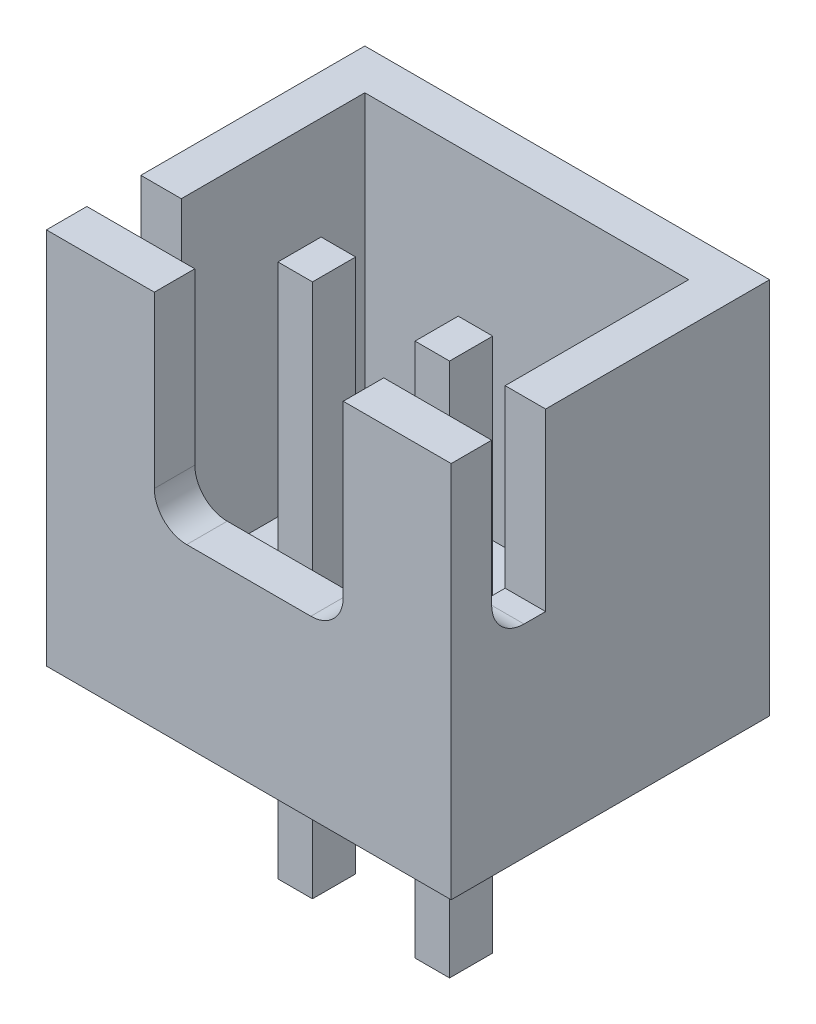
SolidWorks part; units mm, degrees
ref_plane "Alzado" through (0, 0, 0) normal (0, 0, 1) x (1, 0, 0)
ref_plane "Planta" through (0, 0, 0) normal (0, 1, 0) x (1, 0, 0)
ref_plane "Vista lateral" through (0, 0, 0) normal (1, 0, 0) x (0, 0, -1)
sketch "Croquis1" plane through (0, 0, 0) normal (0, 1, 0) x (1, 0, 0)
  line L0 (-2.48, 3.37) -> (5.02, 3.37)
  line L1 (5.02, 3.37) -> (5.02, -2.53)
  line L2 (5.02, -2.53) -> (-2.48, -2.53)
  line L3 (-2.48, -2.53) -> (-2.48, 3.37)
  line L4 (1.27, -2.53) -> (1.27, 2.1284) construction
  line L5 (-0.32, -0.4) -> (0.32, -0.4)
  line L6 (-0.32, -0.4) -> (-0.32, 0.4)
  line L7 (-0.32, 0.4) -> (0.32, 0.4)
  line L8 (0.32, -0.4) -> (0.32, 0.4)
  line L9 (-0.32, -0.4) -> (0.32, 0.4) construction
  line L10 (-0.32, 0.4) -> (0.32, -0.4) construction
  line L11 (2.86, -0.4) -> (2.86, 0.4)
  line L12 (2.86, -0.4) -> (2.22, -0.4)
  line L13 (2.22, -0.4) -> (2.22, 0.4)
  line L14 (2.86, 0.4) -> (2.22, 0.4)
  point P5 (0, 0)
  dimension "D1" = 7.5
  dimension "D2" = 5.9
  dimension "D3" = 3.37
  dimension "D4" = 2.48
  dimension "D5" = 0.8
  dimension "D6" = 0.64
extrude "Saliente-Extruir1" add sketch "Croquis1" along normal blind 1
sketch "Croquis2" plane through (0, 1, 0) normal (0, 1, 0) x (1, 0, 0)
  line L1 (-1.73, -1.78) -> (4.27, -1.78)
  line L2 (-1.73, -1.78) -> (-1.73, 2.62)
  line L3 (-1.73, 2.62) -> (4.27, 2.62)
  line L4 (-2.48, 3.37) -> (-2.48, -2.53)
  line L5 (-2.48, -2.53) -> (5.02, -2.53)
  line L6 (5.02, -2.53) -> (5.02, 3.37)
  line L7 (5.02, 3.37) -> (-2.48, 3.37)
  line L8 (-2.48, 3.37) -> (-2.48, -2.53)
  line L9 (-2.48, -2.53) -> (5.02, -2.53)
  line L10 (5.02, -2.53) -> (5.02, 3.37)
  line L11 (5.02, 3.37) -> (-2.48, 3.37)
  line L12 (4.27, -1.78) -> (4.27, 2.62)
  line L13 (-1.73, -1.78) -> (4.27, 2.62) construction
  line L14 (-1.73, 2.62) -> (4.27, -1.78) construction
  point P2 (1.27, 0.42)
  dimension "D2" = 0.75
  dimension "D3" = 0.75
  dimension "D4" = 0.75
  dimension "D5" = 0.75
  dimension "D1" = 0
extrude "Saliente-Extruir2" add sketch "Croquis2" along normal blind 6
sketch "Croquis3" plane through (-2.48, 0, 0) normal (-1, 0, 0) x (0, 0, 1)
  line L0 (1.78, 7) -> (1.78, 4.35)
  line L1 (-3.37, 7) -> (2.53, 7) construction
  line L2 (0.78, 3.75) -> (0.78, 7)
  line L3 (2.53, 7) -> (2.53, 0) construction
  line L4 (1.18, 3.75) -> (0.78, 3.75)
  line L5 (0.78, 7) -> (1.78, 7)
  arc A1 (1.18, 3.75) -> (1.78, 4.35) centre (1.18, 4.35) ccw
  dimension "D4" = 0.6
  dimension "D1" = 0.75
  dimension "D2" = 1
  dimension "D3" = 3.25
extrude "Cortar-Extruir1" cut sketch "Croquis3" against normal blind 9
sketch "Croquis4" plane through (0, 0, 2.53) normal (0, 0, 1) x (1, 0, 0)
  line L0 (-0.48, 3.85) -> (-0.48, 7)
  line L1 (-2.48, 7) -> (5.02, 7) construction
  line L3 (3.02, 3.85) -> (3.02, 7)
  line L4 (5.02, 7) -> (5.02, 0) construction
  line L5 (1.27, 0) -> (1.27, 7) construction
  line L6 (-2.48, 0) -> (5.02, 0) construction
  line L7 (-0.48, 7) -> (3.02, 7)
  line L9 (1.2665, 3.25) -> (2.42, 3.25)
  line L11 (1.2665, 3.25) -> (0.12, 3.25)
  arc A0 (2.42, 3.25) -> (3.02, 3.85) centre (2.42, 3.85) ccw
  arc A1 (0.12, 3.25) -> (-0.48, 3.85) centre (0.12, 3.85) cw
  point P1 (1.27, 3.25)
  point P18 (1.27, 3.25)
  dimension "D2" = 0.6
  dimension "D1" = 2
  dimension "D3" = 3.75
extrude "Cortar-Extruir2" cut sketch "Croquis4" against normal blind 2
sketch "Croquis5" plane through (0, 0, 0) normal (0, 1, 0) x (1, 0, 0)
  line L0 (2.86, -0.4) -> (2.86, 0.4) construction
  line L1 (2.22, -0.4) -> (2.86, -0.4) construction
  line L2 (2.22, 0.4) -> (2.22, -0.4) construction
  line L3 (2.86, 0.4) -> (2.22, 0.4) construction
  line L4 (0.32, 0.4) -> (-0.32, 0.4) construction
  line L5 (0.32, -0.4) -> (0.32, 0.4) construction
  line L6 (-0.32, -0.4) -> (0.32, -0.4) construction
  line L7 (-0.32, 0.4) -> (-0.32, -0.4) construction
  line L8 (2.86, -0.4) -> (2.86, 0.4)
  line L9 (2.22, -0.4) -> (2.86, -0.4)
  line L10 (2.22, 0.4) -> (2.22, -0.4)
  line L11 (2.86, 0.4) -> (2.22, 0.4)
  line L12 (0.32, 0.4) -> (-0.32, 0.4)
  line L13 (0.32, -0.4) -> (0.32, 0.4)
  line L14 (-0.32, -0.4) -> (0.32, -0.4)
  line L15 (-0.32, 0.4) -> (-0.32, -0.4)
extrude "Saliente-Extruir3" add sketch "Croquis5" along normal blind 6.5 and the other way blind 3.4
